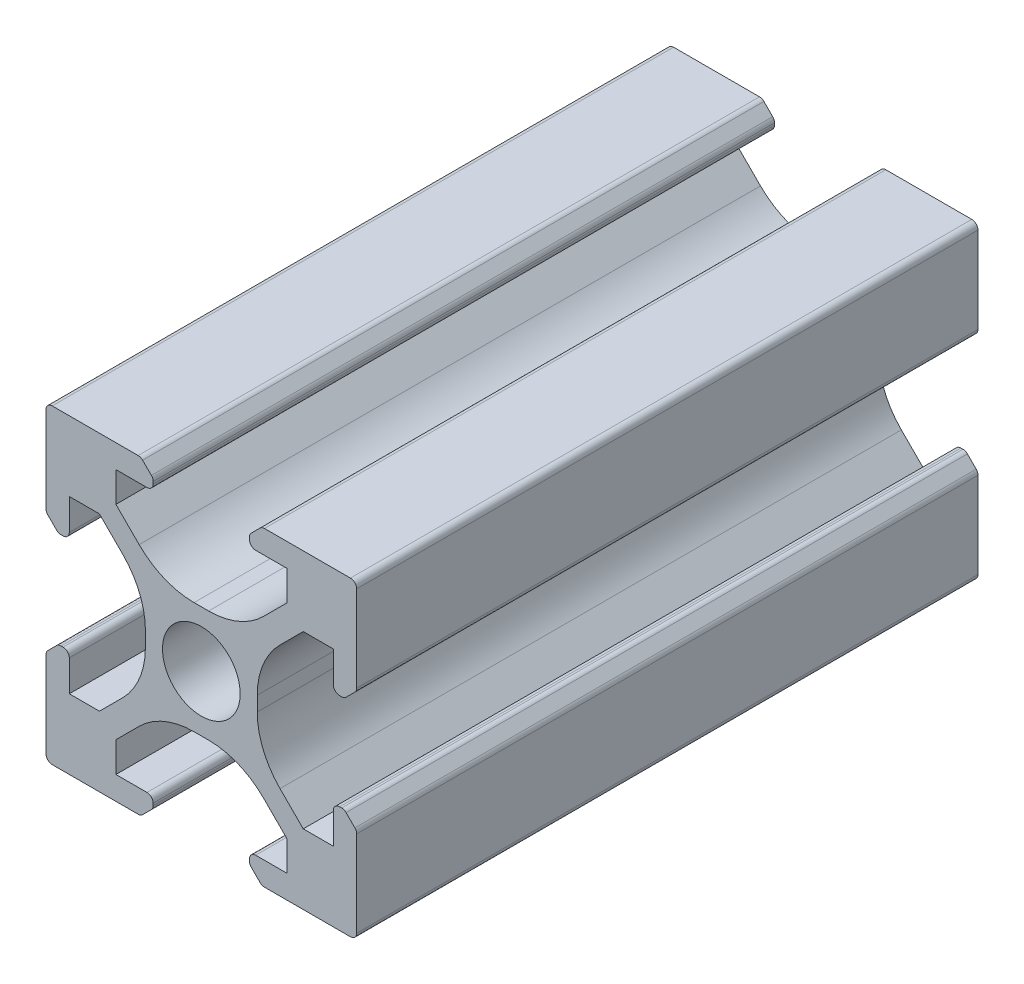
SolidWorks part; units mm, degrees
material "6063-T83"
ref_plane "Plano frontal" through (0, 0, 0) normal (0, 0, 1) x (1, 0, 0)
ref_plane "Plano superior" through (0, 0, 0) normal (0, 1, 0) x (1, 0, 0)
ref_plane "Plano direito" through (0, 0, 0) normal (1, 0, 0) x (0, 0, -1)
sketch "Esboço1" plane through (0, 0, 0) normal (0, 0, 1) x (1, 0, 0)
  line L0 (-9.0343, 3.1) -> (-8.9, 3.1)
  line L3 (-10, 10) -> (-4.0657, 10)
  line L5 (-10, -10) -> (10, 10) construction
  line L6 (-10, 10) -> (10, -10) construction
  line L7 (-8.5, 3.5) -> (-8.5, 5.5)
  line L8 (-10, 0) -> (10, 0) construction
  line L9 (0, 10) -> (0, -10) construction
  line L12 (-8.5, 5.5) -> (-6.5607, 5.5)
  line L15 (-6.5607, 5.5) -> (-5.0645, 4.0038)
  line L16 (-3.6, 0.4683) -> (-3.6, 0)
  line L17 (-0.4683, 3.6) -> (0, 3.6)
  line L18 (-5.5, 6.5607) -> (-4.0038, 5.0645)
  line L21 (-5.5, 8.5) -> (-5.5, 6.5607)
  line L24 (-3.5, 8.5) -> (-5.5, 8.5)
  line L25 (-3.1, 9.0343) -> (-3.1, 8.9)
  line L44 (-10, 4.0657) -> (-10, 10)
  line L45 (-9.8828, 3.7828) -> (-9.3172, 3.2172)
  line L46 (-3.7828, 9.8828) -> (-3.2172, 9.3172)
  line L47 (-3.6, 0) -> (-2.5, 0)
  line L48 (0, 3.6) -> (0, 2.5)
  arc A0 (-3.5, 8.5) -> (-3.1, 8.9) centre (-3.5, 8.9) ccw
  arc A1 (-3.7828, 9.8828) -> (-4.0657, 10) centre (-4.0657, 9.6) ccw
  arc A2 (-10, 4.0657) -> (-9.8828, 3.7828) centre (-9.6, 4.0657) ccw
  arc A3 (-8.5, 3.5) -> (-8.9, 3.1) centre (-8.9, 3.5) cw
  arc A4 (-3.2172, 9.3172) -> (-3.1, 9.0343) centre (-3.5, 9.0343) cw
  arc A5 (-9.3172, 3.2172) -> (-9.0343, 3.1) centre (-9.0343, 3.5) ccw
  arc A6 (-3.6, 0.4683) -> (-5.0645, 4.0038) centre (-8.6, 0.4683) ccw
  arc A7 (-4.0038, 5.0645) -> (-0.4683, 3.6) centre (-0.4683, 8.6) ccw
  circle A8 centre (0, 0) radius 2.5
  point P6 (-10, 3.1)
  point P28 (-3.1, 8.5)
  point P31 (-3.1, 10)
  point P33 (-3.9, 10)
  point P36 (-10, 3.9)
  point P39 (-8.5, 3.1)
  point P42 (-3.1, 9.2)
  point P45 (-9.2, 3.1)
  point P48 (-3.6, 2.5393)
  point P51 (-2.5393, 3.6)
  dimension "D5" = 10
  dimension "D9" = 0.4
  dimension "D10" = 0.4
  dimension "D11" = 5
  dimension "D12" = 5
  dimension "D13" = 5
  dimension "D1" = 6.9
  dimension "D2" = 1.5
  dimension "D3" = 3.6
  dimension "D4" = 1.5
  dimension "D6" = 2.4
  dimension "D7" = 3.6
  dimension "D8" = 45
extrude "Ressalto-extrusão1" add sketch "Esboço1" along normal blind 40
sketch "Esboço3" plane through (0, 0, 0) normal (1, 0, 0) x (0, 0, -1)
  line L0 (0, 0) -> (-40, 0) construction
  line L1 (-40, 2.5) -> (-40, 0) construction
pattern_circular "PadrãoCircular1" count 4 every 90 about axis through (0, 0, 0) along (0, 0, 1) of "Ressalto-extrusão1"
fillet "Filete1" radius 0.4 4 edges at (-10, -10, 20) (-10, 10, 20) (10, -10, 20) (10, 10, 20)
